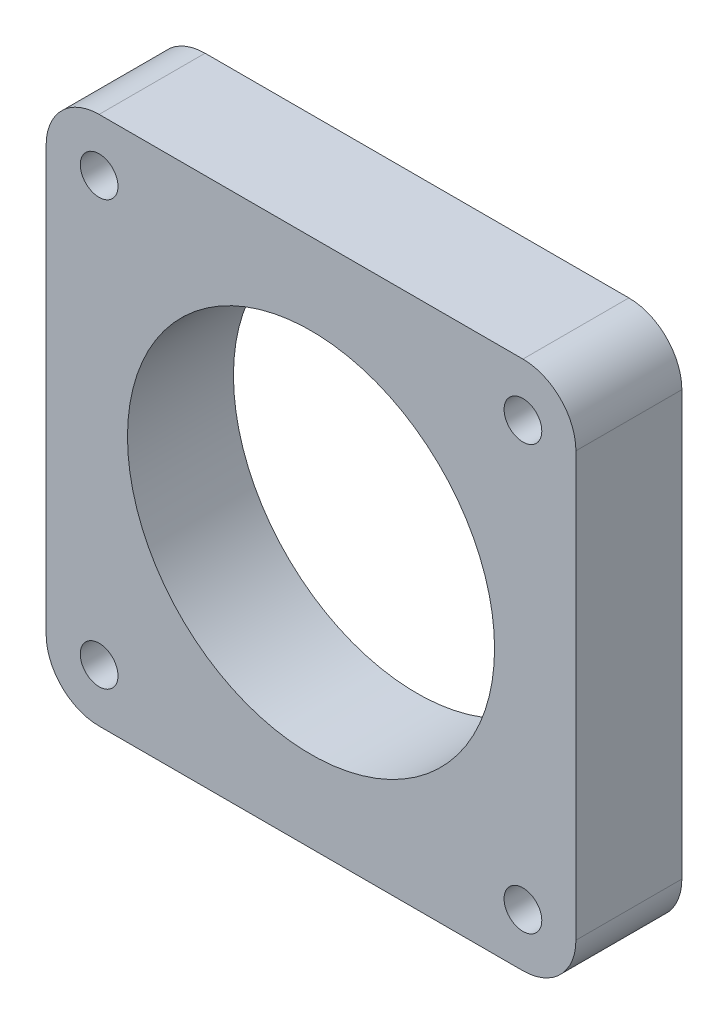
SolidWorks part; units mm, degrees
ref_plane "Front Plane" through (0, 0, 0) normal (0, 0, 1) x (1, 0, 0)
ref_plane "Top Plane" through (0, 0, 0) normal (0, 1, 0) x (1, 0, 0)
ref_plane "Right Plane" through (0, 0, 0) normal (1, 0, 0) x (0, 0, -1)
sketch "Sketch1" plane through (0, 0, 0) normal (0, 0, 1) x (1, 0, 0)
  line L5 (12.7, 12.7) -> (-12.7, -12.7) construction
  line L6 (12.7, 12.7) -> (12.7, 15.875) construction
  line L19 (-12.7, 12.7) -> (-12.7, -12.7) construction
  line L28 (-12.7, -12.7) -> (12.7, -12.7) construction
  line L31 (12.7, -12.7) -> (12.7, 12.7) construction
  line L32 (-12.7, 12.7) -> (12.7, 12.7) construction
  line L33 (-15.875, -15.875) -> (15.875, -15.875)
  line L34 (-15.875, -15.875) -> (-15.875, 15.875)
  line L35 (15.875, -15.875) -> (15.875, 15.875)
  line L36 (-15.875, 15.875) -> (15.875, 15.875)
  line L37 (-15.875, -15.875) -> (15.875, 15.875) construction
  line L38 (15.875, -15.875) -> (-15.875, 15.875) construction
  circle A13 centre (0, 0) radius 11
  circle A25 centre (-12.7, 12.7) radius 1.1303
  circle A26 centre (-12.7, -12.7) radius 1.1303
  circle A27 centre (12.7, -12.7) radius 1.1303
  circle A28 centre (12.7, 12.7) radius 1.1303
  dimension "D9" = 22
  dimension "D3" = 2.2606
  dimension "D1" = 25.4
  dimension "D2" = 31.75
extrude "Boss-Extrude1" add sketch "Sketch1" along normal blind 6.35
fillet "Fillet1" radius 3.175 4 edges at (-15.875, 15.875, 3.175) (-15.875, -15.875, 3.175) (15.875, -15.875, 3.175) (15.875, 15.875, 3.175)
